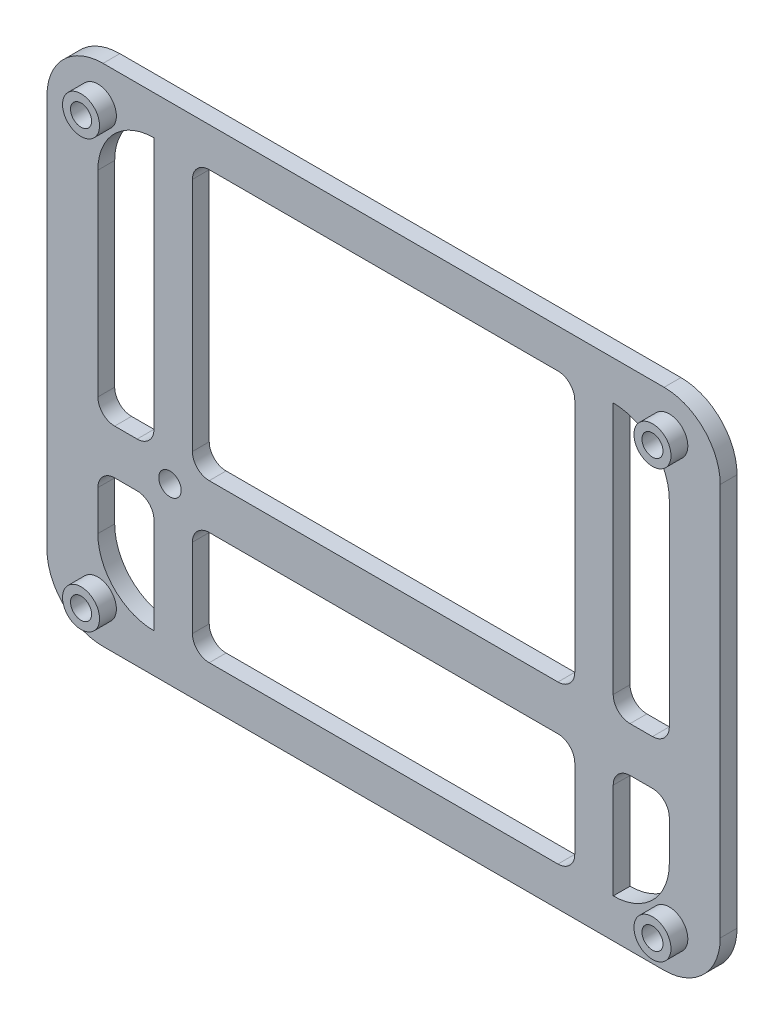
SolidWorks part; units mm, degrees
ref_plane "Ön Düzlem" through (0, 0, 0) normal (0, 0, 1) x (1, 0, 0)
ref_plane "Üst Düzlem" through (0, 0, 0) normal (0, 1, 0) x (1, 0, 0)
ref_plane "Sağ Düzlem" through (0, 0, 0) normal (1, 0, 0) x (0, 0, -1)
sketch "Çizim1" plane through (0, 0, 0) normal (0, 0, 1) x (1, 0, 0)
  line L0 (-31.075, -38.05) -> (31.075, -38.05)
  line L1 (-50, 45) -> (50, 45)
  line L2 (-60, 35) -> (-60, -35)
  line L3 (-50, -45) -> (50, -45)
  line L4 (60, 35) -> (60, -35)
  line L5 (50.925, 28.05) -> (50.925, -6.95)
  line L6 (-31.075, 38.05) -> (31.075, 38.05)
  line L7 (-54.835, 42.15) -> (38.1873, 42.15) construction
  line L8 (-54.835, 42.15) -> (-54.835, -42.15) construction
  line L9 (-54.835, -42.15) -> (54.835, -42.15) construction
  line L10 (54.835, 42.15) -> (54.835, -42.15) construction
  line L11 (-50.925, 28.05) -> (-50.925, -6.95)
  line L12 (-40.925, -13.95) -> (-34.075, -13.95) construction
  line L13 (-38.075, -17.95) -> (-38.075, -11.95) construction
  line L14 (-47.925, -9.95) -> (-43.925, -9.95)
  line L15 (-47.925, -17.95) -> (-43.925, -17.95)
  line L16 (-40.925, 38.05) -> (-40.925, -6.95)
  line L17 (-34.075, 35.05) -> (-34.075, -6.95)
  line L18 (-40.925, -20.95) -> (-40.925, -38.05)
  line L19 (-50.925, -20.95) -> (-50.925, -28.05)
  line L20 (-34.075, -20.95) -> (-34.075, -35.05)
  line L21 (-31.075, -17.95) -> (31.075, -17.95)
  line L22 (-31.075, -9.95) -> (31.075, -9.95)
  line L23 (50.925, -20.95) -> (50.925, -28.05)
  line L24 (0, 45) -> (0, -45) construction
  line L25 (34.075, -20.95) -> (34.075, -35.05)
  line L26 (40.925, -20.95) -> (40.925, -38.05)
  line L27 (40.925, 38.05) -> (40.925, -6.95)
  line L28 (34.075, 35.05) -> (34.075, -6.95)
  line L35 (43.925, -9.95) -> (47.925, -9.95)
  line L36 (43.925, -17.95) -> (47.925, -17.95)
  circle A0 centre (-50.925, 38.05) radius 1.875
  circle A1 centre (50.925, 38.05) radius 1.875
  circle A2 centre (-50.925, -38.05) radius 1.875
  circle A3 centre (50.925, -38.05) radius 1.875
  arc A4 (-60, -35) -> (-50, -45) centre (-50, -35) ccw
  arc A5 (50, -45) -> (60, -35) centre (50, -35) ccw
  arc A6 (60, 35) -> (50, 45) centre (50, 35) ccw
  arc A7 (-60, 35) -> (-50, 45) centre (-50, 35) cw
  circle A8 centre (-38.075, -13.95) radius 2
  arc A9 (-50.925, 28.05) -> (-40.925, 38.05) centre (-40.925, 28.05) cw
  arc A10 (40.925, 38.05) -> (50.925, 28.05) centre (40.925, 28.05) cw
  arc A11 (50.925, -28.05) -> (40.925, -38.05) centre (40.925, -28.05) cw
  arc A12 (-50.925, -28.05) -> (-40.925, -38.05) centre (-40.925, -28.05) ccw
  arc A13 (-31.075, -9.95) -> (-34.075, -6.95) centre (-31.075, -6.95) cw
  arc A14 (50.925, -6.95) -> (47.925, -9.95) centre (47.925, -6.95) cw
  arc A15 (47.925, -17.95) -> (50.925, -20.95) centre (47.925, -20.95) cw
  arc A16 (-31.075, -38.05) -> (-34.075, -35.05) centre (-31.075, -35.05) cw
  arc A17 (-31.075, -17.95) -> (-34.075, -20.95) centre (-31.075, -20.95) ccw
  arc A18 (-40.925, -20.95) -> (-43.925, -17.95) centre (-43.925, -20.95) ccw
  arc A19 (-50.925, -20.95) -> (-47.925, -17.95) centre (-47.925, -20.95) cw
  arc A20 (-50.925, -6.95) -> (-47.925, -9.95) centre (-47.925, -6.95) ccw
  arc A21 (-43.925, -9.95) -> (-40.925, -6.95) centre (-43.925, -6.95) ccw
  arc A22 (-34.075, 35.05) -> (-31.075, 38.05) centre (-31.075, 35.05) cw
  arc A23 (43.925, -17.95) -> (40.925, -20.95) centre (43.925, -20.95) ccw
  arc A24 (31.075, -38.05) -> (34.075, -35.05) centre (31.075, -35.05) ccw
  arc A25 (34.075, -20.95) -> (31.075, -17.95) centre (31.075, -20.95) ccw
  arc A26 (34.075, -6.95) -> (31.075, -9.95) centre (31.075, -6.95) cw
  arc A27 (43.925, -9.95) -> (40.925, -6.95) centre (43.925, -6.95) cw
  arc A28 (34.075, 35.05) -> (31.075, 38.05) centre (31.075, 35.05) ccw
  point P0 (0, 0)
  point P6 (0, 0)
  point P21 (-60, -45)
  point P26 (60, 45)
  point P29 (-60, 45)
  point P57 (-34.075, -9.95)
  point P65 (50.925, -17.95)
  point P70 (-34.075, -17.95)
  point P75 (-50.925, -17.95)
  dimension "D7" = 3.75
  dimension "D12" = 10
  dimension "D13" = 4
  dimension "D16" = 10
  dimension "D21" = 3
  dimension "D22" = 3
  dimension "D1" = 120
  dimension "D2" = 90
  dimension "D3" = 109.67
  dimension "D4" = 84.3
  dimension "D5" = 2.85
  dimension "D6" = 5.165
  dimension "D8" = 3.91
  dimension "D9" = 4.1
  dimension "D14" = 89
  dimension "D15" = 52
  dimension "D17" = 4
  dimension "D18" = 4
  dimension "D19" = 2.85
  dimension "D20" = 4
  dimension "D23" = 76.1
  dimension "D10" = 2
  dimension "D11" = 2
extrude "Yükseklik-Ekstrüzyon2" add sketch "Çizim1" along normal blind 3
sketch "Çizim2" plane through (0, 0, 0) normal (0, 0, -1) x (-1, 0, 0)
  line L0 (-53.3591, -36.0107) -> (-53.9081, -39.1383)
  line L1 (48.4909, -36.0107) -> (47.9419, -39.1383)
  line L2 (47.9419, -39.1383) -> (50.376, -41.1776)
  line L3 (50.376, -41.1776) -> (53.3591, -40.0893)
  line L4 (53.3591, -40.0893) -> (53.9081, -36.9617)
  line L5 (53.9081, -36.9617) -> (51.474, -34.9224)
  line L6 (51.474, -34.9224) -> (48.4909, -36.0107)
  line L7 (-53.9081, -39.1383) -> (-51.474, -41.1776)
  line L8 (-51.474, -41.1776) -> (-48.4909, -40.0893)
  line L9 (-48.4909, -40.0893) -> (-47.9419, -36.9617)
  line L10 (-47.9419, -36.9617) -> (-50.376, -34.9224)
  line L11 (-50.376, -34.9224) -> (-53.3591, -36.0107)
  line L12 (48.4909, 40.0893) -> (47.9419, 36.9617)
  line L13 (47.9419, 36.9617) -> (50.376, 34.9224)
  line L14 (50.376, 34.9224) -> (53.3591, 36.0107)
  line L15 (53.3591, 36.0107) -> (53.9081, 39.1383)
  line L16 (53.9081, 39.1383) -> (51.474, 41.1776)
  line L17 (51.474, 41.1776) -> (48.4909, 40.0893)
  line L18 (-53.3591, 40.0893) -> (-53.9081, 36.9617)
  line L19 (-53.9081, 36.9617) -> (-51.474, 34.9224)
  line L20 (-51.474, 34.9224) -> (-48.4909, 36.0107)
  line L21 (-48.4909, 36.0107) -> (-47.9419, 39.1383)
  line L22 (-47.9419, 39.1383) -> (-50.376, 41.1776)
  line L23 (-50.376, 41.1776) -> (-53.3591, 40.0893)
  circle A0 centre (50.925, -38.05) radius 2.75 construction
  dimension "D1" = 5.5
  dimension "D2" = 2
  dimension "D3" = 2
extrude "Kes-Ekstrüzyon1" cut sketch "Çizim2" against normal blind 2.4
sketch "Çizim3" plane through (0, 0, 3) normal (0, 0, 1) x (1, 0, 0)
  circle A0 centre (-50.925, 38.05) radius 1.875
  circle A1 centre (-50.925, 38.05) radius 3.3
  circle A2 centre (50.925, 38.05) radius 3.3
  circle A3 centre (50.925, 38.05) radius 1.875
  circle A4 centre (-50.925, -38.05) radius 3.3
  circle A5 centre (-50.925, -38.05) radius 1.875
  circle A6 centre (50.925, -38.05) radius 3.3
  circle A7 centre (50.925, -38.05) radius 1.875
  dimension "D1" = 2
  dimension "D2" = 2
extrude "Yükseklik-Ekstrüzyon3" add sketch "Çizim3" along normal blind 3
